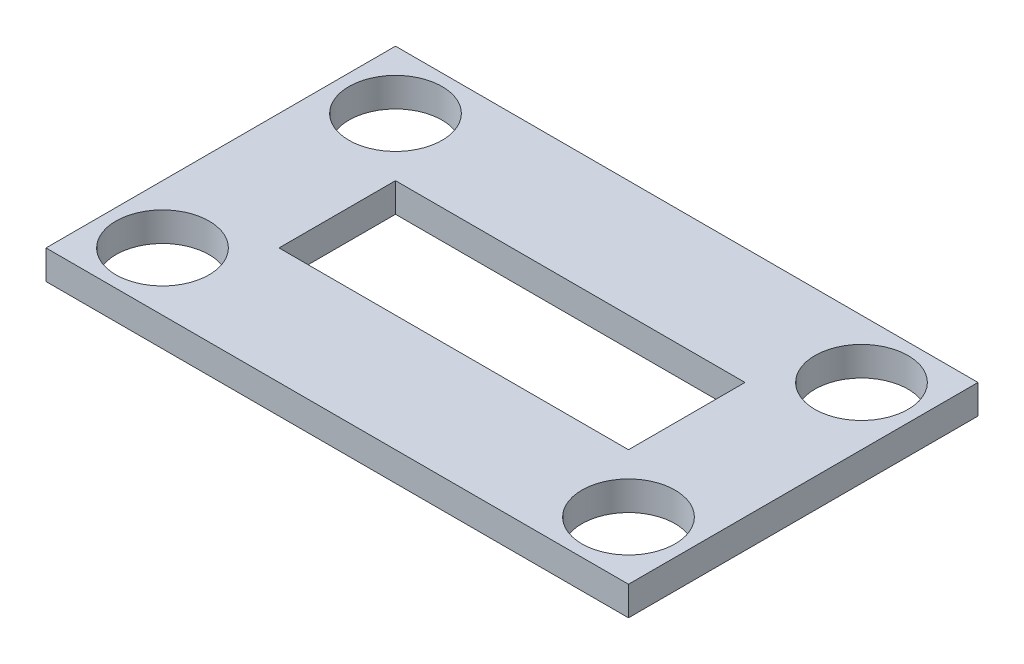
SolidWorks part; units mm, degrees
ref_plane "Front Plane" through (0, 0, 0) normal (0, 0, 1) x (1, 0, 0)
ref_plane "Top Plane" through (0, 0, 0) normal (0, 1, 0) x (1, 0, 0)
ref_plane "Right Plane" through (0, 0, 0) normal (1, 0, 0) x (0, 0, -1)
sketch "Sketch2" plane through (0, 0, 0) normal (0, 1, 0) x (1, 0, 0)
  line L0 (20, 10) -> (20, 15) construction
  line L1 (-20, 10) -> (20, 10)
  line L2 (-20, 10) -> (-20, -10)
  line L3 (-20, -10) -> (20, -10)
  line L4 (20, 10) -> (20, -10)
  line L5 (-20, 10) -> (20, -10) construction
  line L6 (-20, -10) -> (20, 10) construction
  line L7 (20, 10) -> (25, 10) construction
  line L8 (-20, -10) -> (-20, -15) construction
  line L9 (-20, -10) -> (-25, -10) construction
  line L11 (-25, -15) -> (25, -15)
  line L12 (25, -15) -> (25, 15)
  line L13 (25, 15) -> (-25, 15)
  line L14 (-25, 15) -> (-25, -15)
  circle A0 centre (-20, -10) radius 4
  circle A1 centre (20, -10) radius 4
  circle A2 centre (20, 10) radius 4
  circle A3 centre (-20, 10) radius 4
  point P0 (0, 0)
  dimension "D3" = 8
  dimension "D1" = 20
  dimension "D2" = 40
  dimension "D4" = 5
extrude "Boss-Extrude1" add sketch "Sketch2" along normal blind 2.5 contours L13 L14 L11 L12 A3 L1 A2 L4 A1 L3 A0 L2 | A3 L2 A0 L3 A1 L4 A2 L1
sketch "Sketch3" plane through (0, 2.5, 0) normal (0, 1, 0) x (1, 0, 0)
  line L0 (15, -5) -> (25, -5) construction
  line L1 (-15, 5) -> (15, 5)
  line L2 (-15, 5) -> (-15, -5)
  line L3 (-15, -5) -> (15, -5)
  line L4 (15, 5) -> (15, -5)
  line L5 (-15, 5) -> (15, -5) construction
  line L6 (-15, -5) -> (15, 5) construction
  line L7 (25, -15) -> (25, 15) construction
  line L8 (15, -5) -> (15, -15) construction
  line L9 (-25, -15) -> (25, -15) construction
  point P0 (0, 0)
  point P10 (15, -4.7645)
  point P14 (14.7788, -5)
  dimension "D1" = 10
extrude "Cut-Extrude1" cut sketch "Sketch3" against normal blind 5
